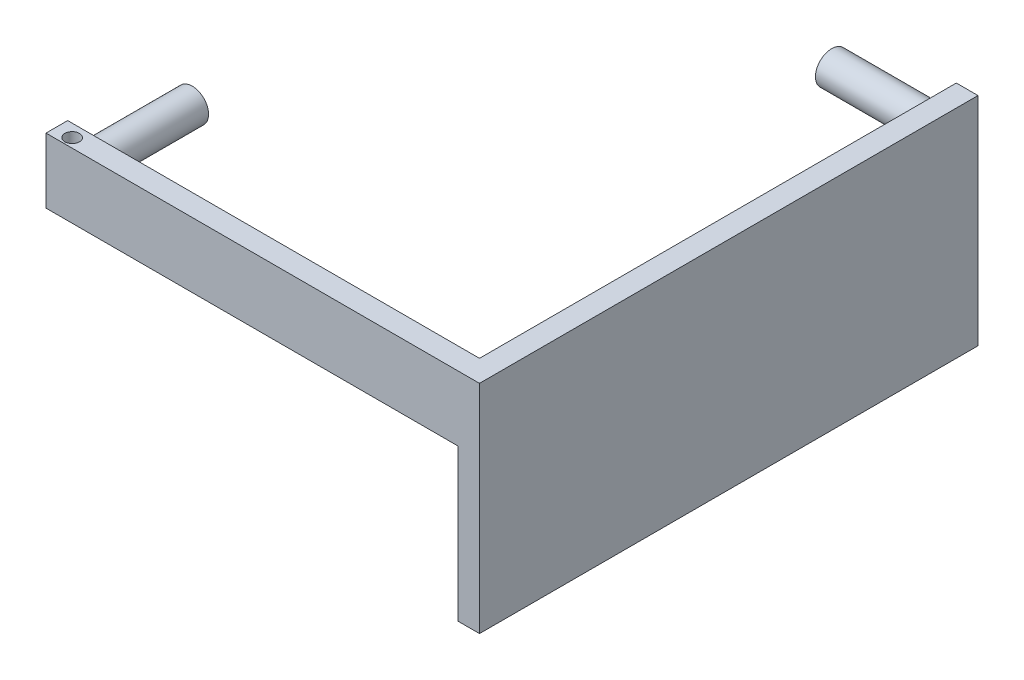
SolidWorks part; units mm, degrees
ref_plane "Front Plane" through (0, 0, 0) normal (0, 0, 1) x (1, 0, 0)
ref_plane "Top Plane" through (0, 0, 0) normal (0, 1, 0) x (1, 0, 0)
ref_plane "Right Plane" through (0, 0, 0) normal (1, 0, 0) x (0, 0, -1)
sketch "Sketch1" plane through (0, 0, 0) normal (0, 1, 0) x (1, 0, 0)
  line L1 (0, 0) -> (200, 0)
  line L2 (0, 0) -> (0, 10)
  line L3 (0, 10) -> (190, 10)
  line L6 (200, 0) -> (200, 230)
  line L7 (200, 230) -> (190, 230)
  line L8 (190, 10) -> (190, 230)
  dimension "D2" = 200
  dimension "1" = 10
  dimension "D3" = 230
  dimension "D4" = 10
extrude "body" add sketch "Sketch1" along normal blind 30
sketch "Sketch2" plane through (0, 0, -10) normal (0, 0, -1) x (-1, 0, 0)
  line L1 (0, 30) -> (0, 0) construction
  line L2 (-190, 30) -> (-190, 0) construction
  circle A0 centre (-7.5, 15) radius 7.5
  point P2 (-7.5, 18.0419)
  point P4 (-18.9476, 15)
  point P8 (-190, 15)
  dimension "D1" = 15
extrude "rotating pin" add sketch "Sketch2" along normal blind 50
sketch "Sketch3" plane through (190, 0, 0) normal (-1, 0, 0) x (0, 0, 1)
  line L2 (-230, 30) -> (-230, 0) construction
  line L3 (0, 30) -> (0, 0) construction
  circle A0 centre (-222.5, 15) radius 7.5
  point P4 (0, 0)
  point P7 (0, 15)
  dimension "D1" = 15
extrude "Boss-Extrude3" add sketch "Sketch3" along normal blind 50
sketch "Sketch4" plane through (0, 0, 0) normal (0, 0, 1) x (1, 0, 0)
  line L0 (0, 30) -> (200, 30) construction
  line L1 (190, 30) -> (200, 30)
  line L2 (190, 30) -> (190, -70)
  line L3 (190, -70) -> (200, -70)
  line L4 (200, 30) -> (200, -70)
  line L5 (200, 30) -> (200, 0) construction
  dimension "D1" = 100
  dimension "D2" = 10
extrude "Boss-Extrude4" add sketch "Sketch4" against normal through all
sketch "Sketch5" plane through (190, 0, 0) normal (-1, 0, 0) x (0, 0, 1)
  line L0 (-230, 15) -> (-230, -70) construction
  line L1 (-230, -70) -> (0, -70) construction
  circle A0 centre (-222.5, -55) radius 7.5
  dimension "D1" = 15
  dimension "D2" = 15
extrude "Boss-Extrude5" add sketch "Sketch5" along normal blind 50
sketch "Sketch6" plane through (0, 30, 0) normal (0, 1, 0) x (1, 0, 0)
  circle A0 centre (7.8315, 4.2163) radius 3.3783
extrude "Cut-Extrude1" cut sketch "Sketch6" against normal blind 10
